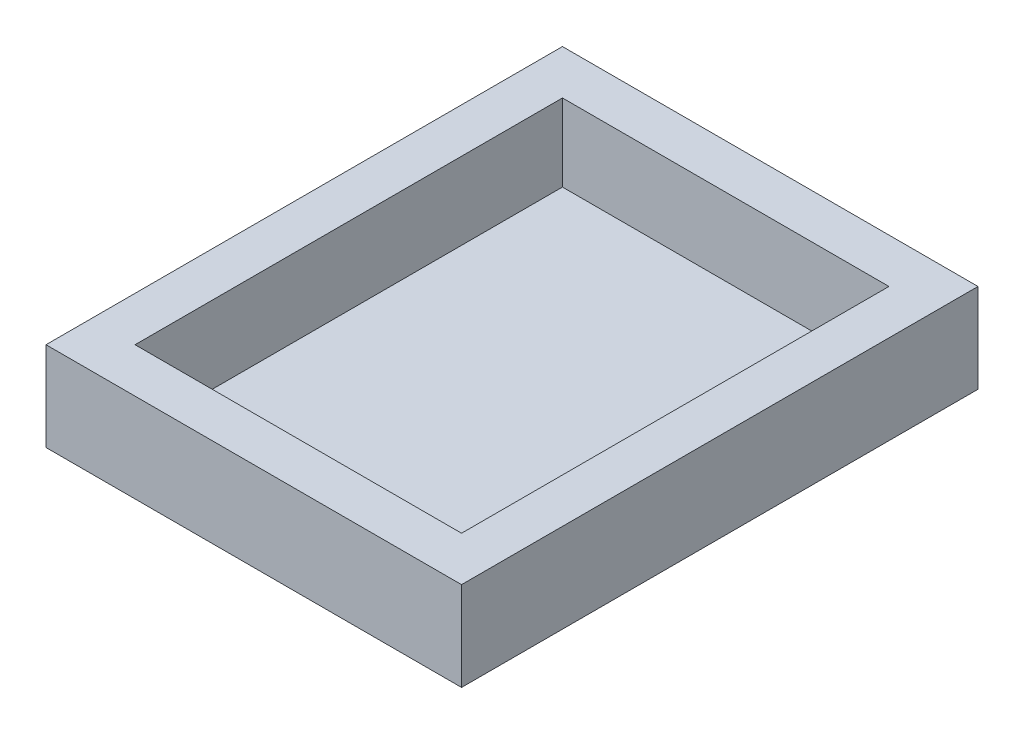
SolidWorks part; units mm, degrees
ref_plane "Front Plane" through (0, 0, 0) normal (0, 0, 1) x (1, 0, 0)
ref_plane "Top Plane" through (0, 0, 0) normal (0, 1, 0) x (1, 0, 0)
ref_plane "Right Plane" through (0, 0, 0) normal (1, 0, 0) x (0, 0, -1)
sketch "Sketch1" plane through (0, 0, 0) normal (0, 1, 0) x (1, 0, 0)
  line L5 (35, -43.5) -> (-35, -43.5)
  line L6 (35, -43.5) -> (35, 43.5)
  line L7 (35, 43.5) -> (-35, 43.5)
  line L8 (-35, -43.5) -> (-35, 43.5)
  line L9 (35, -43.5) -> (-35, 43.5) construction
  line L10 (35, 43.5) -> (-35, -43.5) construction
  point P0 (0, 0)
  dimension "D1" = 87
  dimension "D2" = 70
extrude "Boss-Extrude1" add sketch "Sketch1" along normal blind 15
sketch "Sketch2" plane through (0, 15, 0) normal (0, 1, 0) x (1, 0, 0)
  line L1 (27.5, -36) -> (-27.5, -36)
  line L2 (27.5, -36) -> (27.5, 36)
  line L3 (27.5, 36) -> (-27.5, 36)
  line L4 (-27.5, -36) -> (-27.5, 36)
  line L5 (27.5, -36) -> (-27.5, 36) construction
  line L6 (27.5, 36) -> (-27.5, -36) construction
  point P0 (0, 0)
  dimension "D1" = 72
  dimension "D2" = 55
extrude "Cut-Extrude1" cut sketch "Sketch2" against normal blind 13
